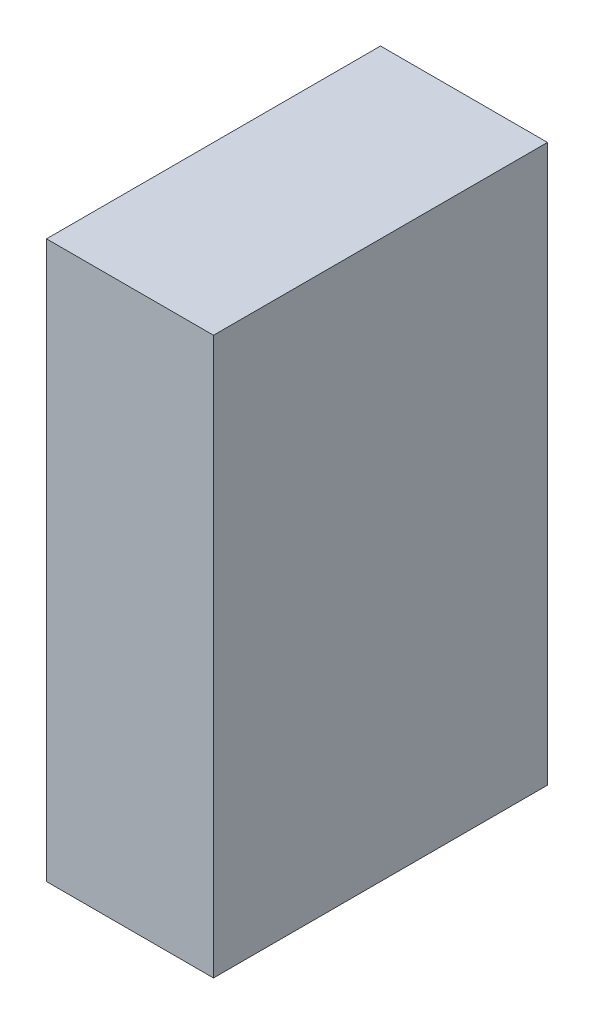
SolidWorks part; units mm, degrees
ref_plane "Front Plane" through (0, 0, 0) normal (0, 0, 1) x (1, 0, 0)
ref_plane "Top Plane" through (0, 0, 0) normal (0, 1, 0) x (1, 0, 0)
ref_plane "Right Plane" through (0, 0, 0) normal (1, 0, 0) x (0, 0, -1)
sketch "草圖1" plane through (0, 0, 0) normal (0, 0, 1) x (1, 0, 0)
  line L0 (-3, -10) -> (3, -10)
  line L1 (3, -10) -> (3, 10)
  line L2 (3, 10) -> (-3, 10)
  line L3 (-3, 10) -> (-3, -10)
extrude "填料-伸長1" add sketch "草圖1" along normal blind 12
